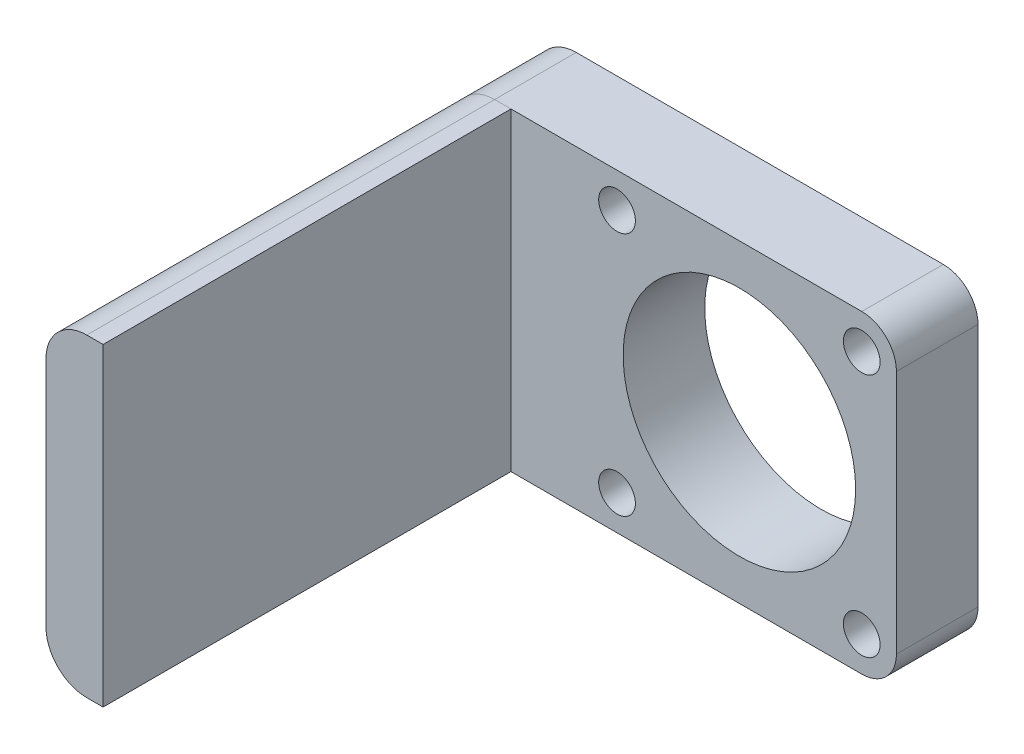
SolidWorks part; units mm, degrees
ref_plane "Front Plane" through (0, 0, 0) normal (0, 0, 1) x (1, 0, 0)
ref_plane "Top Plane" through (0, 0, 0) normal (0, 1, 0) x (1, 0, 0)
ref_plane "Right Plane" through (0, 0, 0) normal (1, 0, 0) x (0, 0, -1)
sketch "Sketch1" plane through (0, 0, 0) normal (0, 0, 1) x (1, 0, 0)
  line L0 (-15, 19.25) -> (-30, 19.25)
  line L2 (-35, 14.25) -> (-35, -14.25)
  line L4 (-15, 19.25) -> (15, 19.25)
  line L5 (19.25, 15) -> (19.25, -15)
  line L6 (15, -19.25) -> (-15, -19.25)
  line L11 (-30, -19.25) -> (-15, -19.25)
  circle A0 centre (0, 0) radius 14.25
  circle A1 centre (15, 15) radius 2.25
  circle A2 centre (-15, 15) radius 2.25
  circle A3 centre (-15, -15) radius 2.25
  circle A4 centre (15, -15) radius 2.25
  arc A8 (19.25, 15) -> (15, 19.25) centre (15, 15) ccw
  arc A9 (15, -19.25) -> (19.25, -15) centre (15, -15) ccw
  circle A12 centre (15, 15) radius 4.25 construction
  circle A13 centre (15, -15) radius 4.25 construction
  arc A19 (-30, -19.25) -> (-35, -14.25) centre (-30, -14.25) cw
  arc A20 (-30, 19.25) -> (-35, 14.25) centre (-30, 14.25) ccw
  point P5 (19.25, 15)
  point P7 (-10.75, 15)
  point P13 (-10.75, -15)
  point P18 (-25.25, 0)
  point P19 (19.25, -15)
  point P20 (-15, 15)
  point P26 (-15, -15)
  point P38 (-29.75, 0)
  point P39 (-20.75, 0)
  dimension "D1" = 2
  dimension "D3" = 5
  dimension "D4" = 2
  dimension "D2" = 2
extrude "Boss-Extrude1" add sketch "Sketch1" along normal blind 10
sketch "Sketch2" plane through (0, 0, 10) normal (0, 0, 1) x (1, 0, 0)
  line L0 (-30, -19.25) -> (15, -19.25) construction
  line L1 (-35, 14.25) -> (-35, -14.25) construction
  line L2 (15, 19.25) -> (-30, 19.25) construction
  line L3 (-30, -19.25) -> (-28, -19.25)
  line L12 (-35, 14.25) -> (-35, -14.25)
  line L13 (-28, 19.25) -> (-30, 19.25)
  line L15 (-28, 0) -> (-28, 19.25)
  line L16 (-28, 0) -> (-28, -19.25)
  arc A14 (-35, -14.25) -> (-30, -19.25) centre (-30, -14.25) ccw construction
  arc A15 (-30, 19.25) -> (-35, 14.25) centre (-30, 14.25) ccw construction
  arc A16 (-35, -14.25) -> (-30, -19.25) centre (-30, -14.25) ccw
  arc A17 (-30, 19.25) -> (-35, 14.25) centre (-30, 14.25) ccw
extrude "Boss-Extrude3" add sketch "Sketch2" along normal blind 50 separate body
